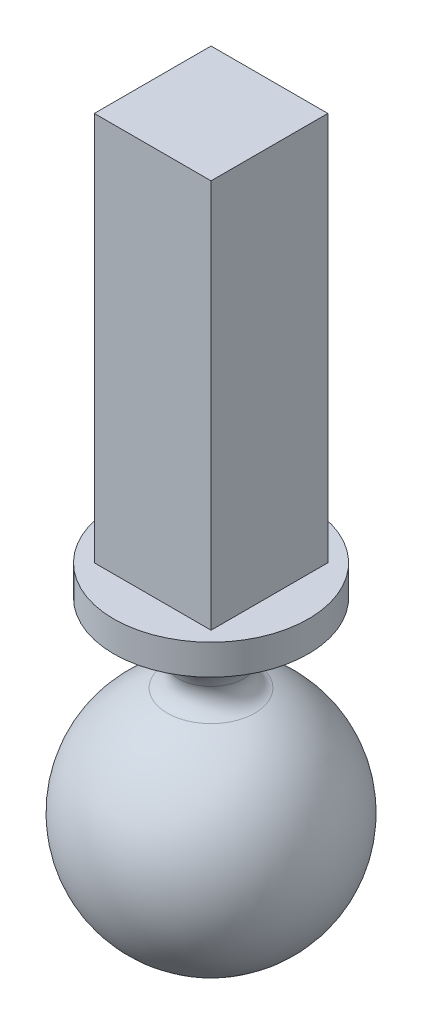
SolidWorks part; units mm, degrees
ref_plane "前视基准面" through (0, 0, 0) normal (0, 0, 1) x (1, 0, 0)
ref_plane "上视基准面" through (0, 0, 0) normal (0, 1, 0) x (1, 0, 0)
ref_plane "右视基准面" through (0, 0, 0) normal (1, 0, 0) x (0, 0, -1)
sketch "草图1" plane through (0, 0, 0) normal (0, 0, 1) x (1, 0, 0)
  line L0 (0, 11.8824) -> (0, -18.1412) construction
  line L1 (-1.6791, 6.8138) -> (-2.2554, 8.4929) construction
  line L2 (-2.2554, 8.4929) -> (-5, 9.5728) construction
  line L3 (-5, 9.5728) -> (-5, 11.1288)
  line L4 (-5, 11.1288) -> (-3.694, 11.1288)
  line L5 (-3.694, 11.1288) -> (0, 11.1288)
  line L6 (0, -6) -> (0, 11.1288)
  arc A0 (0, -6) -> (-2.25, 5.5622) centre (0, 0) cw
  arc A1 (-1.6791, 6.8138) -> (-2.25, 5.5622) centre (-2.6249, 6.4892) cw
  spline S0 degree 2 poles (-1.6791, 6.8138) (-2.2554, 8.4929) (-5, 9.5728) knots 0 0 0 1 1 1
  dimension "D1" = 6
  dimension "D3" = 1
  dimension "D2" = 5
revolve "旋转1" add sketch "草图1" angle 360 about L0
sketch "草图2" plane through (0, 11.1288, 0) normal (0, 1, 0) x (1, 0, 0)
  line L1 (-3, 3) -> (3, 3)
  line L2 (-3, 3) -> (-3, -3)
  line L3 (-3, -3) -> (3, -3)
  line L4 (3, 3) -> (3, -3)
  line L5 (-3, 3) -> (3, -3) construction
  line L6 (-3, -3) -> (3, 3) construction
  point P0 (0, 0)
  dimension "D1" = 6
  dimension "D2" = 6
extrude "凸台-拉伸1" add sketch "草图2" along normal blind 20
